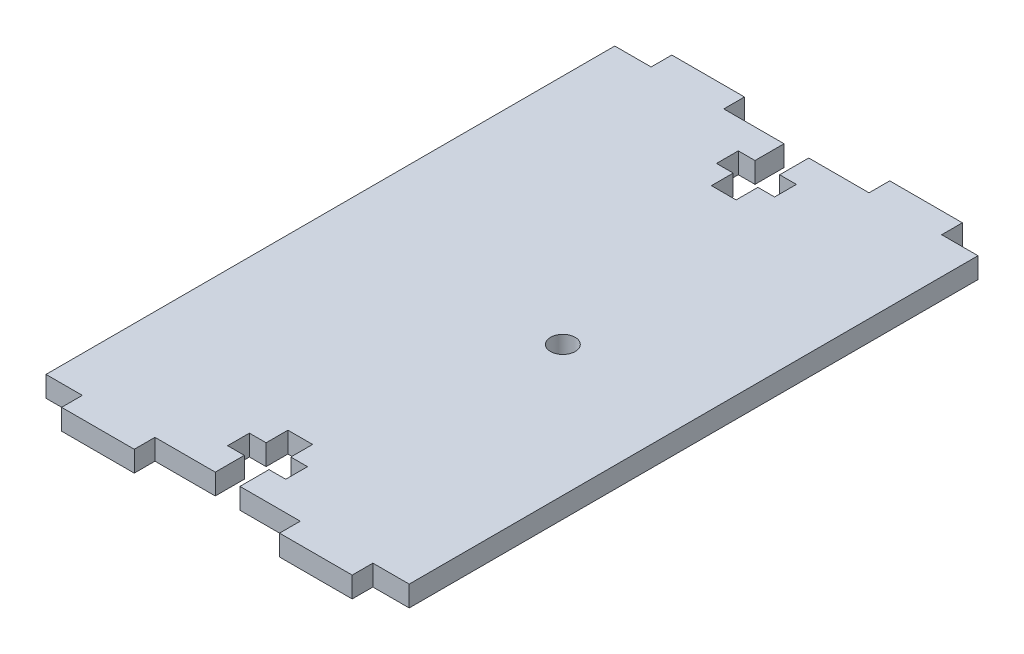
SolidWorks part; units mm, degrees
material "Pine"
ref_plane "Front" through (0, 0, 0) normal (0, 0, 1) x (1, 0, 0)
ref_plane "Top" through (0, 0, 0) normal (0, 1, 0) x (1, 0, 0)
ref_plane "Right" through (0, 0, 0) normal (1, 0, 0) x (0, 0, -1)
sketch "Sketch1" plane through (0, 0, 0) normal (0, 1, 0) x (1, 0, 0)
  line L1 (-25, 39.15) -> (25, 39.15)
  line L2 (-25, 39.15) -> (-25, -39.15)
  line L3 (-25, -39.15) -> (25, -39.15)
  line L4 (25, 39.15) -> (25, -39.15)
  line L5 (-25, 39.15) -> (25, -39.15) construction
  line L6 (-25, -39.15) -> (25, 39.15) construction
  point P0 (0, 0)
  dimension "D1" = 50
  dimension "D2" = 78.3
extrude "Boss-Extrude1" add sketch "Sketch1" along normal blind 2.85
sketch "Sketch2" plane through (0, 2.85, 0) normal (0, 1, 0) x (1, 0, 0)
  line L0 (25, 0) -> (7, 0) construction
  line L1 (25, -39.15) -> (25, 39.15) construction
  circle A0 centre (7, 0) radius 1.7
  dimension "D1" = 3.4
  dimension "D2" = 18
extrude "Cut-Extrude1" cut sketch "Sketch2" against normal through all
sketch "Sketch3" plane through (0, 2.85, 0) normal (0, 1, 0) x (1, 0, 0)
  line L0 (-4, 35.15) -> (-1.7, 35.15)
  line L1 (-4, 35.15) -> (-4, 32.15)
  line L2 (-4, 32.15) -> (-1.7, 32.15)
  line L3 (4, 35.15) -> (4, 32.15)
  line L4 (-1.7, 29.15) -> (1.7, 29.15)
  line L5 (-1.7, 29.15) -> (-1.7, 32.15)
  line L6 (-1.7, 39.15) -> (1.7, 39.15)
  line L7 (1.7, 29.15) -> (1.7, 32.15)
  line L8 (-1.7, 35.15) -> (-1.7, 39.15)
  line L9 (1.7, 35.15) -> (4, 35.15)
  line L10 (1.7, 35.15) -> (1.7, 39.15)
  line L11 (1.7, 32.15) -> (4, 32.15)
  line L12 (0, 29.15) -> (0, 0) construction
  line L13 (25, 39.15) -> (-25, 39.15) construction
  point P4 (-2.1471, 25.2905)
  dimension "D1" = 3.4
  dimension "D2" = 3
  dimension "D3" = 8
  dimension "D4" = 10
  dimension "D5" = 3
extrude "Cut-Extrude2" cut sketch "Sketch3" against normal through all
sketch "Sketch4" plane through (0, 2.85, 0) normal (0, 1, 0) x (1, 0, 0)
  line L0 (-1.7, 39.15) -> (-25, 39.15) construction
  line L1 (-20, 39.15) -> (-10, 39.15)
  line L2 (-20, 39.15) -> (-20, 42)
  line L3 (-20, 42) -> (-10, 42)
  line L4 (-10, 39.15) -> (-10, 42)
  line L5 (25, 39.15) -> (1.7, 39.15) construction
  line L6 (10, 39.15) -> (20, 39.15)
  line L7 (10, 39.15) -> (10, 42)
  line L8 (10, 42) -> (20, 42)
  line L9 (20, 39.15) -> (20, 42)
  line L10 (-25, 39.15) -> (-25, -39.15) construction
  line L11 (-10, 39.15) -> (0, 0) construction
  line L12 (0, 0) -> (10, 39.15) construction
  dimension "D1" = 2.85
  dimension "D2" = 10
  dimension "D3" = 5
extrude "Boss-Extrude2" add sketch "Sketch4" against normal blind 2.85
mirror "Mirror1" about plane through (0, 0, 0) normal (0, 0, 1) of "Cut-Extrude2", "Boss-Extrude2"
